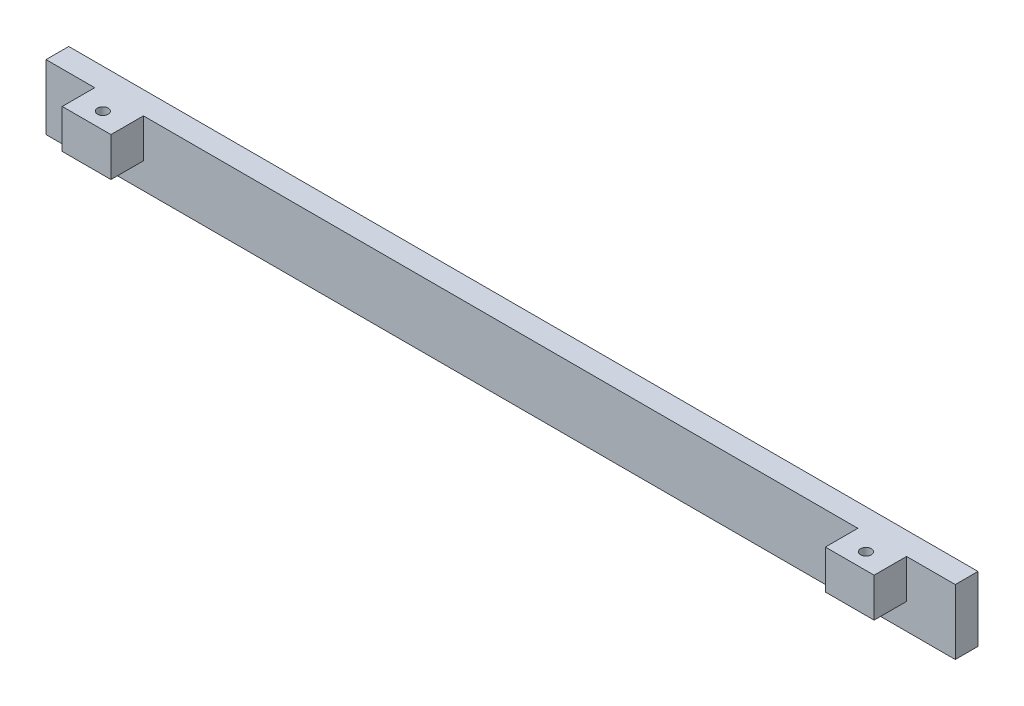
SolidWorks part; units mm, degrees
material "1060 合金"
ref_plane "前视基准面" through (0, 0, 0) normal (0, 0, 1) x (1, 0, 0)
ref_plane "上视基准面" through (0, 0, 0) normal (0, 1, 0) x (1, 0, 0)
ref_plane "右视基准面" through (0, 0, 0) normal (1, 0, 0) x (0, 0, -1)
other "斜边"
sketch "草图1" plane through (0, 0, 0) normal (1, 0, 0) x (0, 0, -1)
  line L1 (-3.5, -10) -> (3.5, -10)
  line L2 (-3.5, -10) -> (-3.5, 10)
  line L3 (-3.5, 10) -> (3.5, 10)
  line L4 (3.5, -10) -> (3.5, 10)
  line L5 (-3.5, -10) -> (3.5, 10) construction
  line L6 (-3.5, 10) -> (3.5, -10) construction
  point P0 (0, 0)
  dimension "D1" = 7
  dimension "D2" = 20
extrude "凸台-拉伸1" add sketch "草图1" along normal mid plane 280
sketch "草图2" plane through (0, 0, 3.5) normal (0, 0, 1) x (1, 0, 0)
  line L0 (0, 0) -> (0, 57.0616) construction
  line L1 (-125, 10) -> (-110, 10)
  line L2 (-125, 10) -> (-125, -2)
  line L3 (-125, -2) -> (-110, -2)
  line L4 (-110, 10) -> (-110, -2)
  line L5 (140, -10) -> (-140, -10) construction
  line L6 (140, 10) -> (-140, 10) construction
  dimension "D1" = 8
  dimension "D2" = 15
  dimension "D3" = 250
extrude "凸台-拉伸2" add sketch "草图2" along normal blind 10
mirror "镜向1" about plane through (0, 0, 0) normal (1, 0, 0) of "凸台-拉伸2"
hole_wizard "M4 螺纹孔1" positions "草图4" profile "草图3" tap size "M4" standard "GB" end condition up to next
sketch "草图4" plane through (0, -2, 0) normal (0, -1, 0) x (-1, 0, 0)
  line L0 (0, 0) -> (0, -40.588) construction
  line L1 (-110, -13.5) -> (-110, -3.5) construction
  line L2 (-117.5, -8.5) -> (-110, -8.5) construction
  point P0 (-117.5, -8.5)
  point P9 (117.5, -8.5)
  dimension "D1" = 235
  dimension "D2" = 7.5
sketch "草图3" plane through (117.5, -2, 8.5) normal (1, 0, 0) x (0, 0, -1)
  line L0 (0, 0) -> (0, 12)
  line L1 (0, 12) -> (1.65, 12)
  line L2 (1.65, 12) -> (1.65, 0)
  line L5 (1.65, 0) -> (0, 0)
  line L11 (0, -6.35) -> (0, 107.95) construction
  dimension "通孔螺纹孔钻头直径" = 3.3
  dimension "通孔螺纹孔钻头深度" = 12
cosmetic thread "孔螺蚊线1" parameters "D2"=4
cosmetic thread "孔螺蚊线2" parameters "D2"=4
sketch "草图5" [suppressed] plane through (0, 0, -3.5) normal (0, 0, -1) x (-1, 0, 0)
  line L0 (0, 0) -> (0, 56.8035) construction
  line L1 (-54, 10) -> (-42, -2)
  line L2 (-145, 10) -> (145, 10) construction
  line L3 (54, 10) -> (42, -2)
  line L4 (-42, -2) -> (42, -2)
  line L5 (-145, -10) -> (145, -10) construction
  dimension "D1" = 8
  dimension "D2" = 45
  dimension "D3" = 84
extrude "切除-拉伸1" [suppressed] cut sketch "草图5" against normal through all and the other way through all flip side to cut
